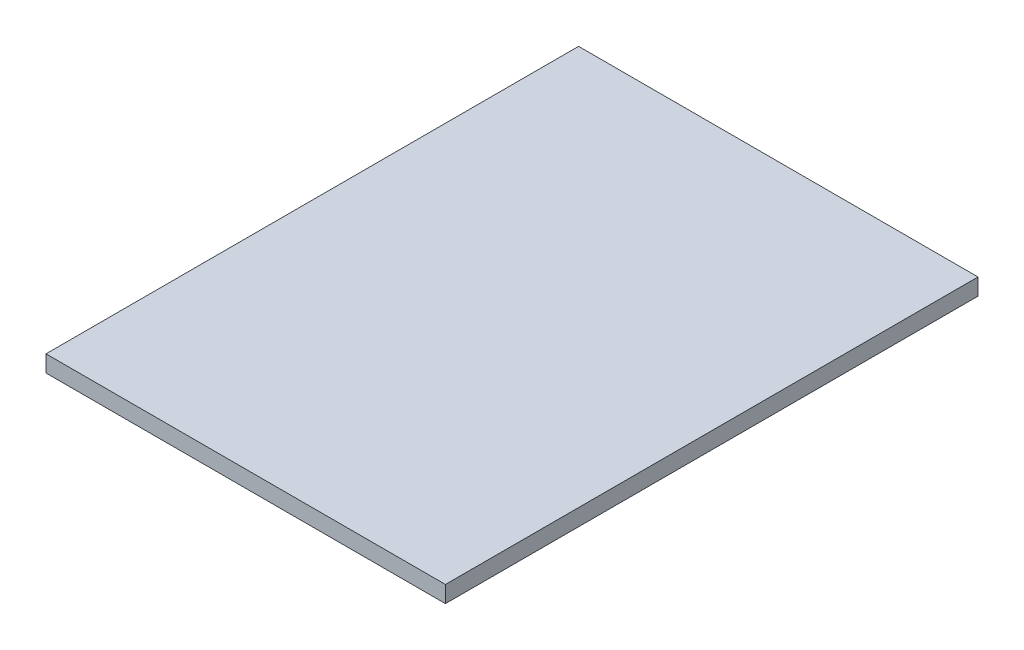
SolidWorks part; units mm, degrees
material "ASTM A36 Steel"
ref_plane "Front Plane" through (0, 0, 0) normal (0, 0, 1) x (1, 0, 0)
ref_plane "Top Plane" through (0, 0, 0) normal (0, 1, 0) x (1, 0, 0)
ref_plane "Right Plane" through (0, 0, 0) normal (1, 0, 0) x (0, 0, -1)
sketch "Sketch1" plane through (0, 0, 0) normal (0, 1, 0) x (1, 0, 0)
  line L1 (-114.3, -152.4) -> (114.3, -152.4)
  line L2 (-114.3, -152.4) -> (-114.3, 152.4)
  line L3 (-114.3, 152.4) -> (114.3, 152.4)
  line L4 (114.3, -152.4) -> (114.3, 152.4)
  line L5 (-114.3, -152.4) -> (114.3, 152.4) construction
  line L6 (-114.3, 152.4) -> (114.3, -152.4) construction
  line L7 (-114.3, 0) -> (114.3, 0) construction
  point P0 (0, 0)
  dimension "D1" = 228.6
  dimension "D2" = 304.8
extrude "Boss-Extrude1" add sketch "Sketch1" along normal blind 9.525
